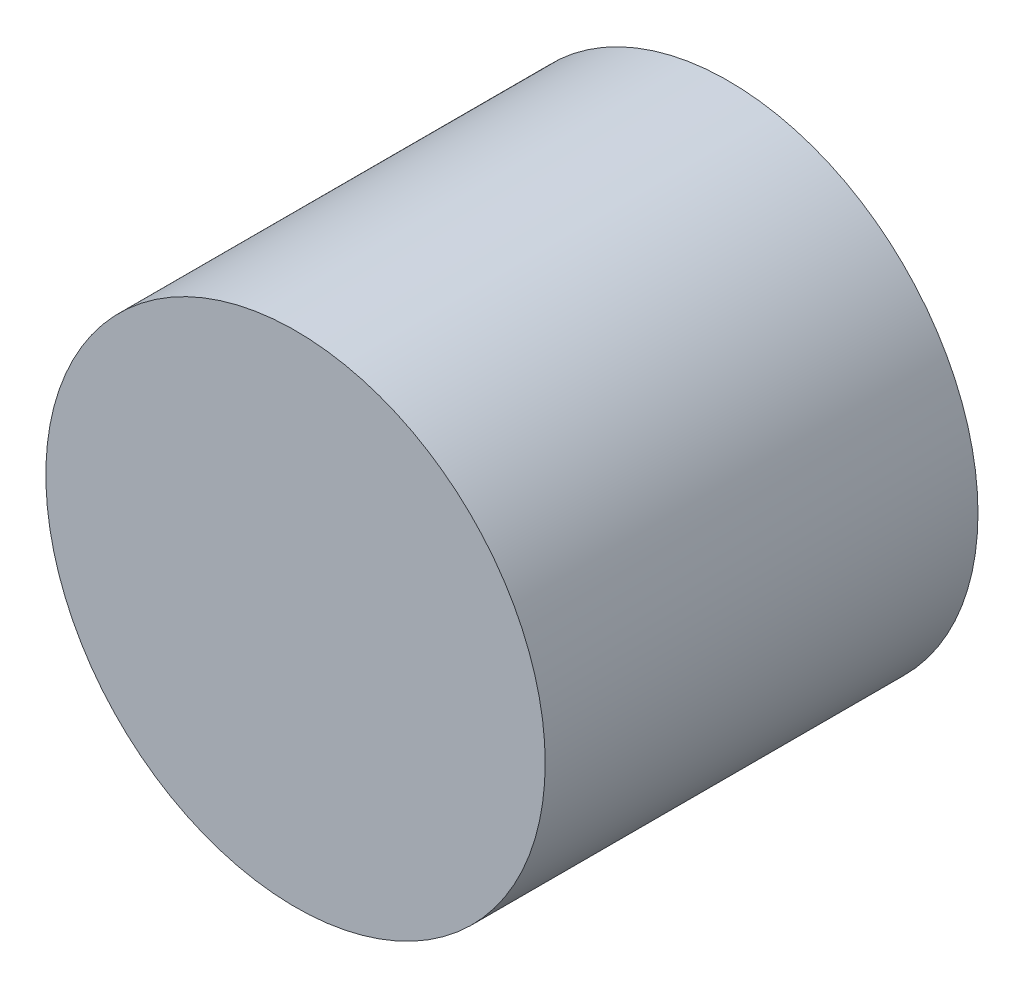
SolidWorks part; units mm, degrees
material "6061 Alloy"
ref_plane "Front Plane" through (0, 0, 0) normal (0, 0, 1) x (1, 0, 0)
ref_plane "Top Plane" through (0, 0, 0) normal (0, 1, 0) x (1, 0, 0)
ref_plane "Right Plane" through (0, 0, 0) normal (1, 0, 0) x (0, 0, -1)
sketch "Sketch1" plane through (0, 0, 0) normal (0, 0, 1) x (1, 0, 0)
  circle A0 centre (0, 0) radius 15
  dimension "D1" = 15
extrude "Boss-Extrude1" add sketch "Sketch1" along normal blind 26
sketch "Sketch5" plane through (0, 0, 0) normal (1, 0, 0) x (0, 0, -1)
  line L0 (0, 0) -> (-26.2851, 0) construction
  circle A0 centre (-13.1426, 0) radius 3
  dimension "D1" = 3
extrude "Cut-Extrude1" cut sketch "Sketch5" against normal blind 23.5
